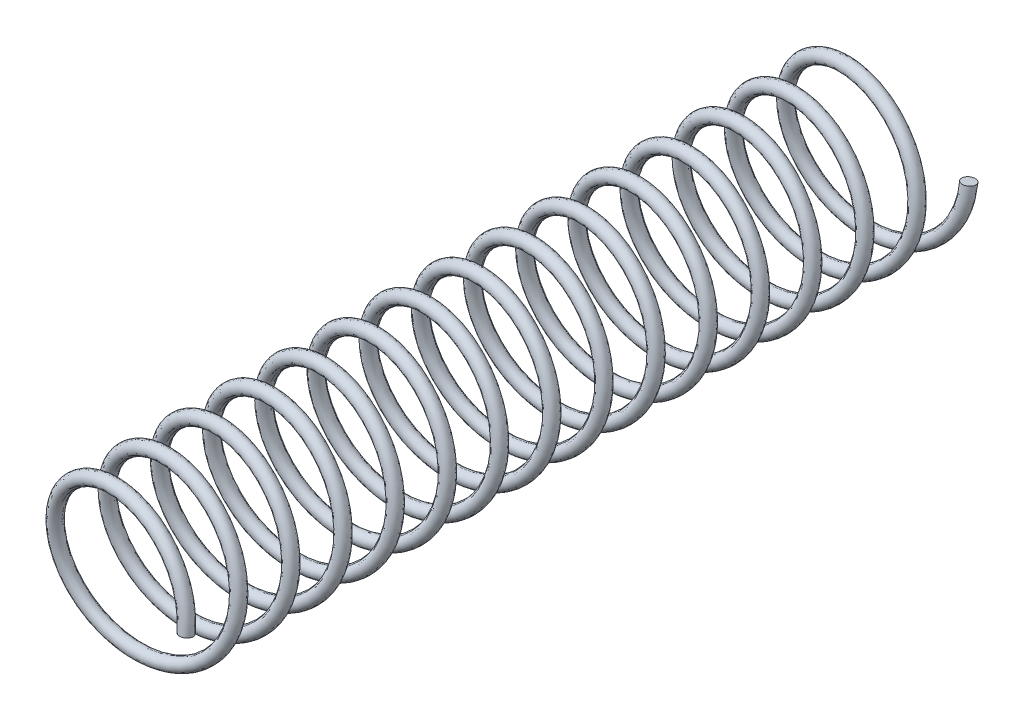
SolidWorks part; units mm, degrees
material "Alloy Steel"
ref_plane "Front Plane" through (0, 0, 0) normal (0, 0, 1) x (1, 0, 0)
ref_plane "Top Plane" through (0, 0, 0) normal (0, 1, 0) x (1, 0, 0)
ref_plane "Right Plane" through (0, 0, 0) normal (1, 0, 0) x (0, 0, -1)
sketch "Sketch1" plane through (0, 0, 0) normal (0, 0, 1) x (1, 0, 0)
  circle A0 centre (0, 0) radius 3
  dimension "D1" = 6
curve "Helix/Spiral1" pitch 2 height 30 turns 15
ref_plane "Plane1" through (3, 0, 30) normal (0, -0.9944, 0.1055) x (-1, 0, 0)
sketch "Sketch3" plane through (3, 0, 30) normal (0, -0.9944, 0.1055) x (-1, 0, 0)
  circle A0 centre (0, 0) radius 0.25
  point P2 (0, 0)
  dimension "D1" = 0.5
sweep "Sweep1" add profiles "Sketch3" path "Helix/Spiral1"
